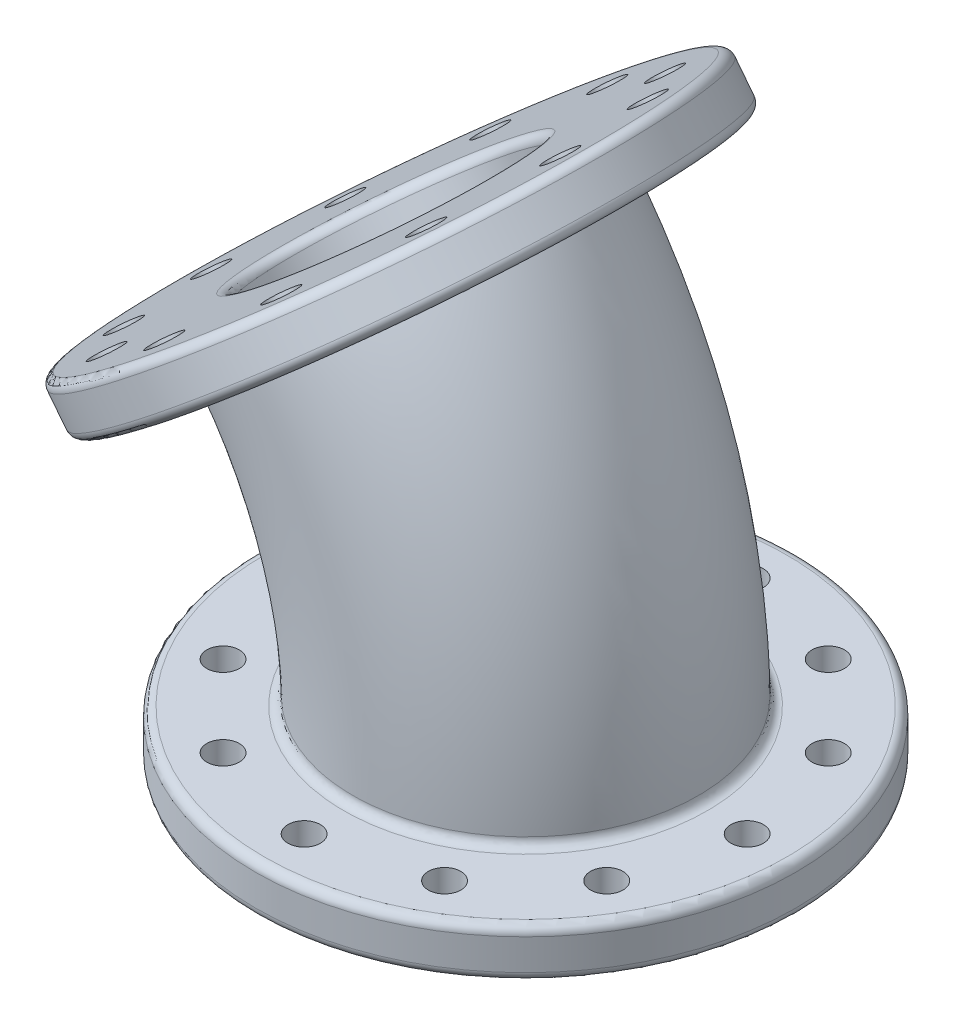
SolidWorks part; units mm, degrees
material "Brass"
ref_plane "Front Plane" through (0, 0, 0) normal (0, 0, 1) x (1, 0, 0)
ref_plane "Top Plane" through (0, 0, 0) normal (0, 1, 0) x (1, 0, 0)
ref_plane "Right Plane" through (0, 0, 0) normal (1, 0, 0) x (0, 0, -1)
sketch "Sketch1" plane through (0, 0, 0) normal (0, 1, 0) x (1, 0, 0)
  circle A0 centre (0, 0) radius 61
  circle A1 centre (0, 50) radius 3.665
  circle A2 centre (0, 0) radius 28
  circle A3 centre (25, 43.3013) radius 3.665
  circle A4 centre (43.3013, 25) radius 3.665
  circle A5 centre (50, 0) radius 3.665
  circle A6 centre (43.3013, -25) radius 3.665
  circle A7 centre (25, -43.3013) radius 3.665
  circle A8 centre (0, -50) radius 3.665
  circle A9 centre (-25, -43.3013) radius 3.665
  circle A10 centre (-43.3013, -25) radius 3.665
  circle A11 centre (-50, 0) radius 3.665
  circle A12 centre (-43.3013, 25) radius 3.665
  circle A13 centre (-25, 43.3013) radius 3.665
  point P6 (0, 0)
  point P31 (0, 0)
  dimension "D1" = 7.33
  dimension "D2" = 33
  dimension "D3" = 56
  dimension "D5" = 11
  dimension "D4" = 12
extrude "Boss-Extrude1" add sketch "Sketch1" along normal blind 11
sketch "Sketch4" plane through (0, 11, 0) normal (0, 1, 0) x (1, 0, 0)
  line L0 (-117, -990.6941) -> (-117, 49009.3059) construction
  circle A0 centre (0, 0) radius 39
  circle A1 centre (0, 0) radius 28 construction
  circle A2 centre (0, 0) radius 28
  dimension "D1" = 11
  dimension "D2" = 78
revolve "Revolve3" add sketch "Sketch4" angle 38 about L0
fillet "Fillet2" radius 2 4 edges at (0, 0, 28) (0, 0, 61) (0, 11, 61) (0, 11, 39)
sketch "Sketch6" plane through (-49.6842, 63.5929, 0) normal (-0.6157, 0.788, 0) x (0.788, 0.6157, 0)
  circle A0 centre (31.575, 0) radius 28 construction
  circle A1 centre (31.575, 0) radius 28
  circle A2 centre (31.575, 0) radius 61
  circle A3 centre (31.575, 50) radius 3.665
  circle A4 centre (56.575, 43.3013) radius 3.665
  circle A5 centre (74.8763, 25) radius 3.665
  circle A6 centre (81.575, 0) radius 3.665
  circle A7 centre (74.8763, -25) radius 3.665
  circle A8 centre (56.575, -43.3013) radius 3.665
  circle A9 centre (31.575, -50) radius 3.665
  circle A10 centre (6.575, -43.3013) radius 3.665
  circle A11 centre (-11.7263, -25) radius 3.665
  circle A12 centre (-18.425, 0) radius 3.665
  circle A13 centre (-11.7263, 25) radius 3.665
  circle A14 centre (6.575, 43.3013) radius 3.665
  point P7 (12.6459, -6.3242)
  point P30 (31.575, 0)
  dimension "D1" = 33
  dimension "D2" = 11
  dimension "D3" = 7.33
  dimension "D4" = 12
extrude "Boss-Extrude4" add sketch "Sketch6" along normal blind 11
fillet "Fillet3" radius 2 4 edges at (-24.8027, 83.0324, 39) (-79.6437, 54.1452, 0) (-72.8714, 45.477, 0) (-53.6393, 74.462, 0)
